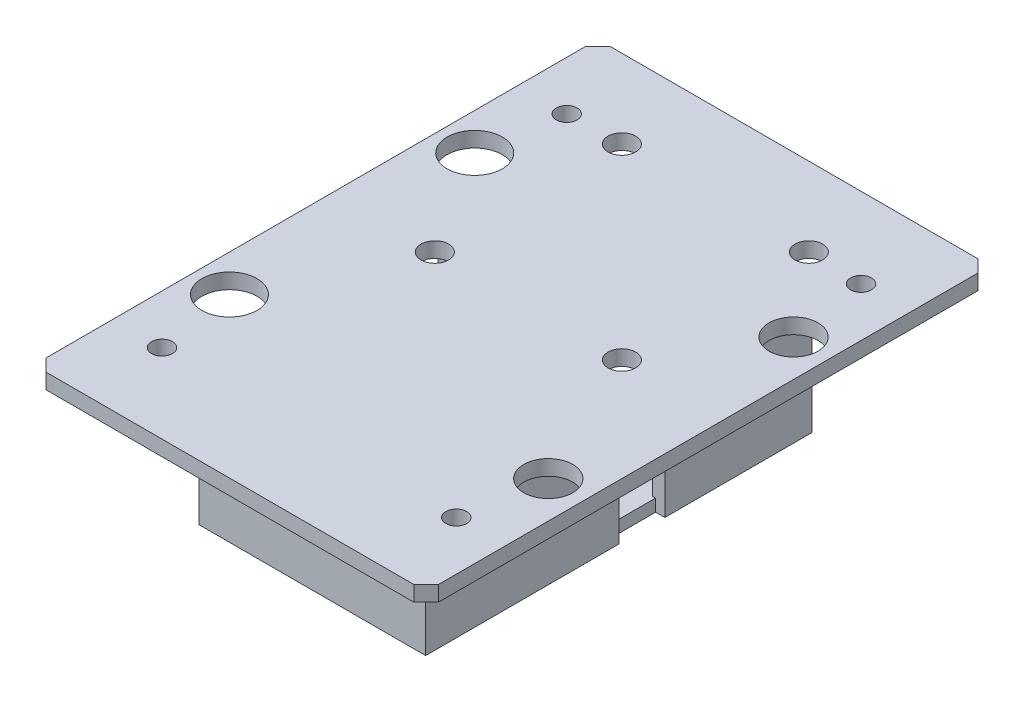
SolidWorks part; units mm, degrees
ref_plane "前视基准面" through (0, 0, 0) normal (0, 0, 1) x (1, 0, 0)
ref_plane "上视基准面" through (0, 0, 0) normal (0, 1, 0) x (1, 0, 0)
ref_plane "右视基准面" through (0, 0, 0) normal (1, 0, 0) x (0, 0, -1)
other "Configuration Table"
sketch "草图1" plane through (0, 0, 0) normal (0, 1, 0) x (1, 0, 0)
  line L0 (-30, -45.917) -> (30, -45.917)
  line L1 (30, -45.917) -> (32, -43.917)
  line L2 (32, -43.917) -> (32, 44.083)
  line L3 (32, 44.083) -> (30, 46.083)
  line L4 (30, 46.083) -> (-30, 46.083)
  line L5 (-30, 46.083) -> (-32, 44.083)
  line L6 (-32, 44.083) -> (-32, -43.917)
  line L7 (-32, -43.917) -> (-30, -45.917)
  line L8 (0, 0) -> (70.5208, 0) construction
  line L9 (0, 0) -> (0, 30.158) construction
  circle A0 centre (-15.25, 2.75) radius 2.25
  circle A1 centre (-15.25, 33.25) radius 2.25
  circle A2 centre (15.25, 2.75) radius 2.25
  circle A3 centre (15.25, 33.25) radius 2.25
  circle A4 centre (-24, -33) radius 1.7
  circle A8 centre (-26, -20) radius 4.5
  circle A9 centre (-26, 20) radius 4.5
  circle A10 centre (26, -20) radius 4
  circle A11 centre (26, 20) radius 4
  circle A12 centre (24, -33) radius 1.7
  circle A13 centre (24, 33) radius 1.7
  circle A14 centre (-24, 33) radius 1.7
  point P36 (0, 0)
  point P40 (-20.3266, 0)
  dimension "D1" = 3.4
  dimension "D2" = 24
  dimension "D3" = 33
extrude "凸台-拉伸1" add sketch "草图1" along normal blind 2.5
sketch "草图2" plane through (0, 0, 0) normal (0, 1, 0) x (1, 0, 0)
  line L1 (12, -30.5) -> (17, -30.5)
  line L2 (12, -30.5) -> (12, 30.5)
  line L3 (12, 30.5) -> (17, 30.5)
  line L4 (17, -30.5) -> (17, 30.5)
  line L5 (-17, -30.5) -> (-12, -30.5)
  line L6 (-17, -30.5) -> (-17, 30.5)
  line L7 (-17, 30.5) -> (-12, 30.5)
  line L8 (-12, -30.5) -> (-12, 30.5)
extrude "凸台-拉伸2" add sketch "草图2" along normal blind 2 from offset 20
sketch "草图3" plane through (0, 0, 0) normal (0, 1, 0) x (1, 0, 0)
  line L1 (16.5, -30.5) -> (18.5, -30.5)
  line L2 (16.5, -30.5) -> (16.5, -1)
  line L3 (16.5, -1) -> (18.5, -1)
  line L4 (18.5, -30.5) -> (18.5, -1)
  line L5 (-18.5, -30.5) -> (-16.5, -30.5)
  line L6 (-18.5, -30.5) -> (-18.5, -1)
  line L7 (-18.5, -1) -> (-16.5, -1)
  line L8 (-16.5, -30.5) -> (-16.5, -1)
  line L9 (16.5, 6.5) -> (18.5, 6.5)
  line L10 (16.5, 6.5) -> (16.5, 30.5)
  line L11 (16.5, 30.5) -> (18.5, 30.5)
  line L12 (18.5, 6.5) -> (18.5, 30.5)
  line L13 (-18.5, 6.5) -> (-16.5, 6.5)
  line L14 (-18.5, 6.5) -> (-18.5, 30.5)
  line L15 (-18.5, 30.5) -> (-16.5, 30.5)
  line L16 (-16.5, 6.5) -> (-16.5, 30.5)
extrude "凸台-拉伸3" add sketch "草图3" along normal blind 20 from offset 20
sketch "草图4" plane through (0, 0, 0) normal (0, 1, 0) x (1, 0, 0)
  line L1 (-18.5, -32.5) -> (18.5, -32.5)
  line L2 (-18.5, -32.5) -> (-18.5, -30)
  line L3 (-18.5, -30) -> (18.5, -30)
  line L4 (18.5, -32.5) -> (18.5, -30)
extrude "凸台-拉伸4" add sketch "草图4" along normal blind 20 from offset 20
